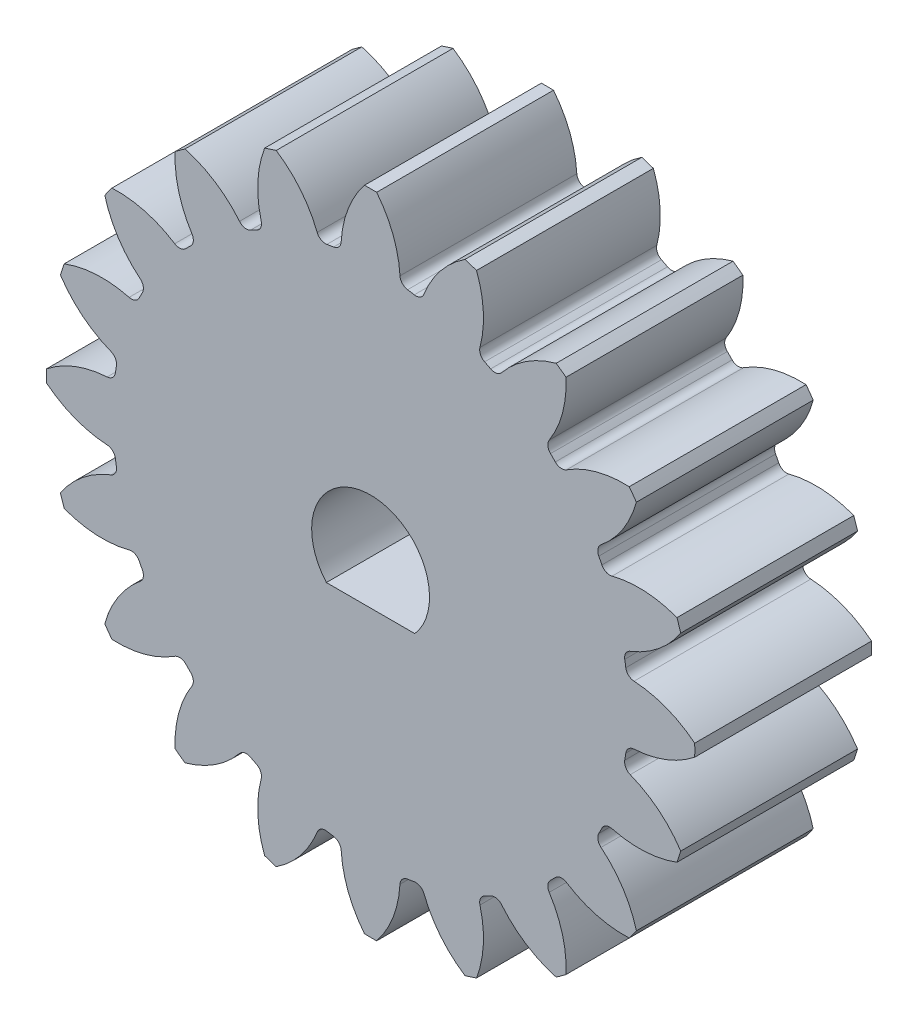
SolidWorks part; units mm, degrees
ref_plane "Front Plane" through (0, 0, 0) normal (0, 0, 1) x (1, 0, 0)
ref_plane "Top Plane" through (0, 0, 0) normal (0, 1, 0) x (1, 0, 0)
ref_plane "Right Plane" through (0, 0, 0) normal (1, 0, 0) x (0, 0, -1)
sketch "Sketch1" plane through (0, 0, 0) normal (1, 0, 0) x (0, 0, -1)
  line L0 (-6, 0) -> (-6, 11)
  line L1 (-6, 11) -> (0, 11)
  line L2 (0, 11) -> (0, 5.85)
  line L3 (0, 5.85) -> (6, 5.85)
  line L4 (6, 5.85) -> (6, 0)
  line L5 (6, 0) -> (-6, 0) construction
  line L6 (-6, 2.5) -> (6, 2.5)
  point P9 (-6, 7.15)
  dimension "OD" = 22
  dimension "Face Width" = 6
  dimension "Hub Width" = 6
  dimension "Hub Diameter" = 11.7
  dimension "For Shaft Diameter" = 5
  dimension "Overall Width" = 12
  dimension "Under Cut Diameter" = 14.3
sketch "Sketch2" plane through (0, 0, 0) normal (0, 0, 1) x (1, 0, 0)
  line L0 (-1.2624, 8.6584) -> (-0.4102, 11)
  line L1 (-0.4102, 11) -> (0.4102, 11)
  line L2 (0.4102, 11) -> (1.2624, 8.6584)
  line L3 (0, 11) -> (0, 0) construction
  line L4 (0, 0) -> (-1.7208, 10.8646) construction
  line L5 (0, 0) -> (1.7208, 10.8646) construction
  line L6 (-3.8763, 7.8446) -> (-3.7893, 10.3349)
  line L7 (-3.7893, 10.3349) -> (-3.0091, 10.5884)
  line L8 (-3.0091, 10.5884) -> (-1.475, 8.6248)
  line L9 (-3.3992, 10.4616) -> (0, 0) construction
  line L11 (-0.4102, 11) -> (0, 11) construction
  line L12 (-0.7854, 9.9691) -> (0.7854, 9.9691) construction
  circle A0 centre (0, 0) radius 10 construction
  circle A2 centre (0, 0) radius 11
  circle A3 centre (0, 0) radius 8.75
  arc A5 (-0.2051, 11) -> (-1.0042, 8.6922) centre (2.6264, 8.7273) ccw
  arc A6 (1.0042, 8.6922) -> (0.2051, 11) centre (-2.6264, 8.7273) ccw
  arc A7 (-1.731, 8.5771) -> (-3.2041, 10.525) centre (-5.1948, 7.4885) ccw
  arc A8 (-0.7854, 9.9691) -> (0.7854, 9.9691) centre (0, 0) cw
  point P3 (0, 10)
  point P5 (3.0902, 9.5106)
  point P9 (5.8779, 8.0902)
  point P10 (8.0902, 5.8779)
  point P11 (9.5106, 3.0902)
  point P12 (10, 0)
  point P13 (9.5106, -3.0902)
  point P14 (8.0902, -5.8779)
  point P15 (5.8779, -8.0902)
  point P16 (3.0902, -9.5106)
  point P17 (0, -10)
  point P18 (-3.0902, -9.5106)
  point P19 (-5.8779, -8.0902)
  point P20 (-8.0902, -5.8779)
  point P21 (-9.5106, -3.0902)
  point P22 (-10, 0)
  point P23 (-9.5106, 3.0902)
  point P24 (-8.0902, 5.8779)
  point P25 (-5.8779, 8.0902)
  point P26 (-3.0902, 9.5106)
  point P31 (0, 0)
  dimension "Gear Pitch Diameter" = 20
  dimension "Pressure Angle" = 20
  dimension "Addendum" = 1
  dimension "Dedendum" = 1.25
  dimension "D1" = 18
  dimension "D2" = 1.5708
  dimension "Number of Teeth" = 20
sketch "Sketch3" plane through (0, 0, 0) normal (1, 0, 0) x (0, 0, -1)
  line L0 (-6, 11) -> (0, 11) construction
  line L1 (6, 5.85) -> (6, 0) construction
  line L2 (0, 5.85) -> (6, 5.85) construction
  line L3 (0, 11) -> (0, 5.85) construction
  line L4 (-6, 0) -> (-6, 11) construction
  line L5 (-6, 2.5) -> (6, 2.5) construction
  line L6 (-6, 11) -> (0, 11)
  line L7 (6, 5.85) -> (6, 2.5)
  line L8 (-6, 5.85) -> (-4.2857, 5.85)
  line L9 (0, 11) -> (0, 7.15)
  line L10 (-6, 2.5) -> (-6, 5.85)
  line L11 (-6, 2.5) -> (6, 2.5)
  line L12 (-6, 7.15) -> (-4.2857, 7.15)
  line L13 (-4.2857, 7.15) -> (-4.2857, 5.85)
  line L14 (0, 7.15) -> (-1.7143, 7.15)
  line L15 (-1.7143, 7.15) -> (-1.7143, 5.85)
  line L16 (-1.7143, 5.85) -> (6, 5.85)
  line L17 (-6, 7.15) -> (-6, 11)
  dimension "D1" = 1.7143
revolve "Revolve1" add sketch "Sketch3" angle 360 about L5
sketch "Sketch4" plane through (0, 0, 6) normal (0, 0, 1) x (1, 0, 0)
  arc A1 (-0.2051, 11) -> (-1.0042, 8.6922) centre (2.6264, 8.7273) ccw construction
  arc A2 (-1.731, 8.5771) -> (-3.2041, 10.525) centre (-5.1948, 7.4885) ccw construction
  arc A3 (-0.2067, 10.9981) -> (-0.9982, 8.939) centre (2.6264, 8.7273) ccw
  arc A4 (-1.813, 8.8099) -> (-3.2021, 10.5236) centre (-5.1948, 7.4885) ccw
  circle A5 centre (0, 0) radius 11 construction
  arc A6 (-0.2067, 10.9981) -> (-3.2021, 10.5236) centre (0, 0) ccw
  circle A7 centre (0, 0) radius 8.75 construction
  arc A8 (-1.2547, 8.6596) -> (-1.4827, 8.6235) centre (0, 0) ccw
  arc A9 (-1.813, 8.8099) -> (-1.4827, 8.6235) centre (-1.5335, 8.9191) ccw
  arc A10 (-1.2547, 8.6596) -> (-0.9982, 8.939) centre (-1.2977, 8.9565) ccw
  dimension "D1" = 0.3
extrude "Cut-Extrude1" cut sketch "Sketch4" against normal through all both and the other way through all
pattern_circular "CirPattern1" count 20 over 360 about axis through (0, 0, 0) along (0, 0, 1) of "Cut-Extrude1"
sketch "Sketch5" plane through (0, 0, 6) normal (0, 0, 1) x (1, 0, 0)
  circle A0 centre (0, 0) radius 7.15
  circle A2 centre (0, 0) radius 2
  dimension "D1" = 4
  dimension "D2" = 14.3
extrude "Boss-Extrude1" add sketch "Sketch5" against normal up to surface (6 mm away) up to face at (-7.15, 0, 0)
sketch "Sketch6" plane through (0, 0, 0) normal (0, 0, -1) x (-1, 0, 0)
  circle A0 centre (0, 0) radius 5.85
  dimension "D1" = 11.7
extrude "Cut-Extrude2" cut sketch "Sketch6" along normal up to next
sketch3d "3DSketch1"
  line L0 (-1.5, -1.3229, 6) -> (1.5, -1.3229, 6)
  line L1 (1.5, -1.3229, 6) -> (1.5, -1.3229, 0)
  line L2 (1.5, -1.3229, 0) -> (-1.5, -1.3229, 0)
  line L3 (-1.5, -1.3229, 0) -> (-1.5, -1.3229, 6)
  circle A0 centre (0, 0, 6) radius 2 construction
  circle A1 centre (0, 0, 0) radius 2 construction
  point P4 (0, 0, 8)
  point P8 (0, 0, 2)
  dimension "D1" = 3
extrude "Boss-Extrude2" add sketch "3DSketch1" along direction (0, 1, 0) on the side of the normal blind 3
equation "\"Dedendum@Sketch2\" = 1.25 /  ( \"Number of Teeth@Sketch2\" / \"Gear Pitch Diameter@Sketch2\" ) "
equation "\"D1@Sketch2\"=360/\"Number of Teeth@Sketch2\""
equation "\"D1@Sketch4\"=.3/(\"Number of Teeth@Sketch2\"/\"Gear Pitch Diameter@Sketch2\")"
equation "\"D1@CirPattern1\"=\"Number of Teeth@Sketch2\""
equation "\"D2@Sketch2\"=1.5708/(\"Number of Teeth@Sketch2\"/\"Gear Pitch Diameter@Sketch2\")"
equation "\"D1@Sketch3\"=\"Face Width@Sketch1\"/3.5"
